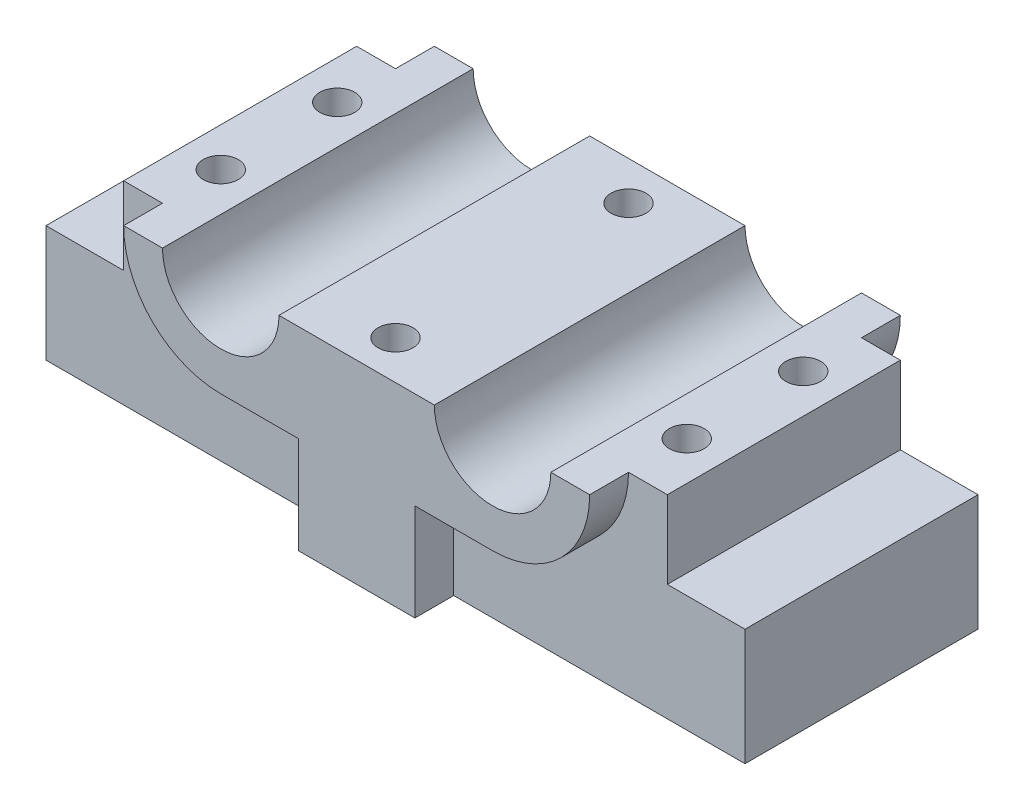
SolidWorks part; units mm, degrees
ref_plane "Front Plane" through (0, 0, 0) normal (0, 0, 1) x (1, 0, 0)
ref_plane "Top Plane" through (0, 0, 0) normal (0, 1, 0) x (1, 0, 0)
ref_plane "Right Plane" through (0, 0, 0) normal (1, 0, 0) x (0, 0, -1)
sketch "Sketch1" plane through (0, 0, 0) normal (0, 0, 1) x (1, 0, 0)
  line L1 (-45, 12.5) -> (45, 12.5)
  line L2 (-45, 12.5) -> (-45, -12.5)
  line L3 (-45, -12.5) -> (45, -12.5)
  line L4 (45, 12.5) -> (45, -12.5)
  line L5 (-45, 12.5) -> (45, -12.5) construction
  line L6 (-45, -12.5) -> (45, 12.5) construction
  point P0 (0, 0)
  dimension "D1" = 90
  dimension "D2" = 25
extrude "Boss-Extrude1" add sketch "Sketch1" along normal mid plane 40
sketch "Sketch2" plane through (0, 0, 20) normal (0, 0, 1) x (1, 0, 0)
  line L0 (45, 12.5) -> (-45, 12.5) construction
  line L1 (-45, 12.5) -> (-35, 12.5)
  line L2 (-45, 12.5) -> (-45, 2.5)
  line L3 (-45, 2.5) -> (-35, 2.5)
  line L4 (-35, 12.5) -> (-35, 2.5)
  line L5 (45, 12.5) -> (35, 12.5)
  line L6 (45, 12.5) -> (45, 2.5)
  line L7 (45, 2.5) -> (35, 2.5)
  line L8 (35, 12.5) -> (35, 2.5)
  dimension "D1" = 10
  dimension "D2" = 10
  dimension "D3" = 10
extrude "Cut-Extrude1" cut sketch "Sketch2" against normal through all and the other way through all
sketch "Sketch3" plane through (0, 0, 20) normal (0, 0, 1) x (1, 0, 0)
  line L1 (35, 12.5) -> (-35, 12.5) construction
  line L3 (-45, -12.5) -> (45, -12.5) construction
  line L5 (45, -12.5) -> (45, 2.5)
  line L6 (45, 2.5) -> (35, 2.5)
  line L7 (35, 2.5) -> (35, 12.5)
  line L8 (35, 12.5) -> (30, 12.5)
  line L9 (17.5, 0) -> (7.5, 0)
  line L10 (7.5, 0) -> (7.5, -12.5)
  line L11 (7.5, -12.5) -> (45, -12.5)
  line L12 (0, -13.75) -> (0, 13.75) construction
  line L13 (-7.5, -12.5) -> (-45, -12.5)
  line L14 (-7.5, 0) -> (-7.5, -12.5)
  line L15 (-17.5, 0) -> (-7.5, 0)
  line L16 (-35, 12.5) -> (-30, 12.5)
  line L17 (-35, 2.5) -> (-35, 12.5)
  line L18 (-45, 2.5) -> (-35, 2.5)
  line L19 (-45, -12.5) -> (-45, 2.5)
  arc A0 (30, 12.5) -> (17.5, 0) centre (17.5, 12.5) cw
  arc A1 (-30, 12.5) -> (-17.5, 0) centre (-17.5, 12.5) ccw
  dimension "D1" = 12.5
  dimension "D2" = 17.5
  dimension "D3" = 7.5
extrude "Cut-Extrude2" cut sketch "Sketch3" against normal blind 5
mirror "Mirror1" about plane through (0, 0, 0) normal (0, 0, 1) of "Cut-Extrude2"
sketch "Sketch4" plane through (0, 0, 20) normal (0, 0, 1) x (1, 0, 0)
  line L0 (30, 12.5) -> (-30, 12.5) construction
  line L1 (25, 12.5) -> (10, 12.5)
  line L2 (-10, 12.5) -> (-25, 12.5)
  arc A0 (25, 12.5) -> (10, 12.5) centre (17.5, 12.5) cw
  arc A1 (-25, 12.5) -> (-10, 12.5) centre (-17.5, 12.5) ccw
  dimension "D1" = 7.5
extrude "Cut-Extrude3" cut sketch "Sketch4" against normal through all
hole_wizard "Hole1" positions "Sketch5" profile "Sketch6" legacy end condition through all
sketch "Sketch5" plane through (0, 12.5, 0) normal (0, 1, 0) x (1, 0, 0)
  point P0 (30, -7.5)
  dimension "D1" = 7.5
  dimension "D2" = 30
sketch "Sketch6" plane through (30, 12.5, 7.5) normal (1, 0, 0) x (0, 0, 1)
  line L0 (0, 0) -> (0, 25)
  line L1 (0, 25) -> (2.25, 25)
  line L2 (2.25, 25) -> (2.25, 0)
  line L3 (2.25, 0) -> (0, 0)
  line L4 (0, 110) -> (0, -10) construction
  dimension "Diameter" = 4.5
  dimension "Depth" = 25
pattern_linear "LPattern1" count 2 spacing 15 along (0, 0, -1) count 2 spacing 60 along (-1, 0, 0) of "Hole1"
mirror "Mirror2" about plane through (0, 0, 0) normal (1, 0, 0) of "LPattern1"
hole_wizard "Hole2" positions "Sketch7" profile "Sketch8" legacy end condition through all
sketch "Sketch7" plane through (0, 12.5, 0) normal (0, 1, 0) x (1, 0, 0)
  line L1 (10, -20) -> (-10, -20) construction
  line L3 (-25, 20) -> (-30, 20) construction
  point P0 (0, -15)
  point P2 (0, 15)
  point P7 (0, 0)
  point P9 (-74.5356, -5.5212)
  point P10 (0, -12.6452)
  point P17 (0, 0)
  point P18 (0, 0)
  dimension "D1" = 5
  dimension "D2" = 5
sketch "Sketch8" plane through (0, 12.5, 15) normal (1, 0, 0) x (0, 0, 1)
  line L0 (0, 0) -> (0, 25)
  line L1 (0, 25) -> (2.25, 25)
  line L2 (2.25, 25) -> (2.25, 0)
  line L3 (2.25, 0) -> (0, 0)
  line L4 (0, 110) -> (0, -10) construction
  dimension "Diameter" = 4.5
  dimension "Depth" = 25
